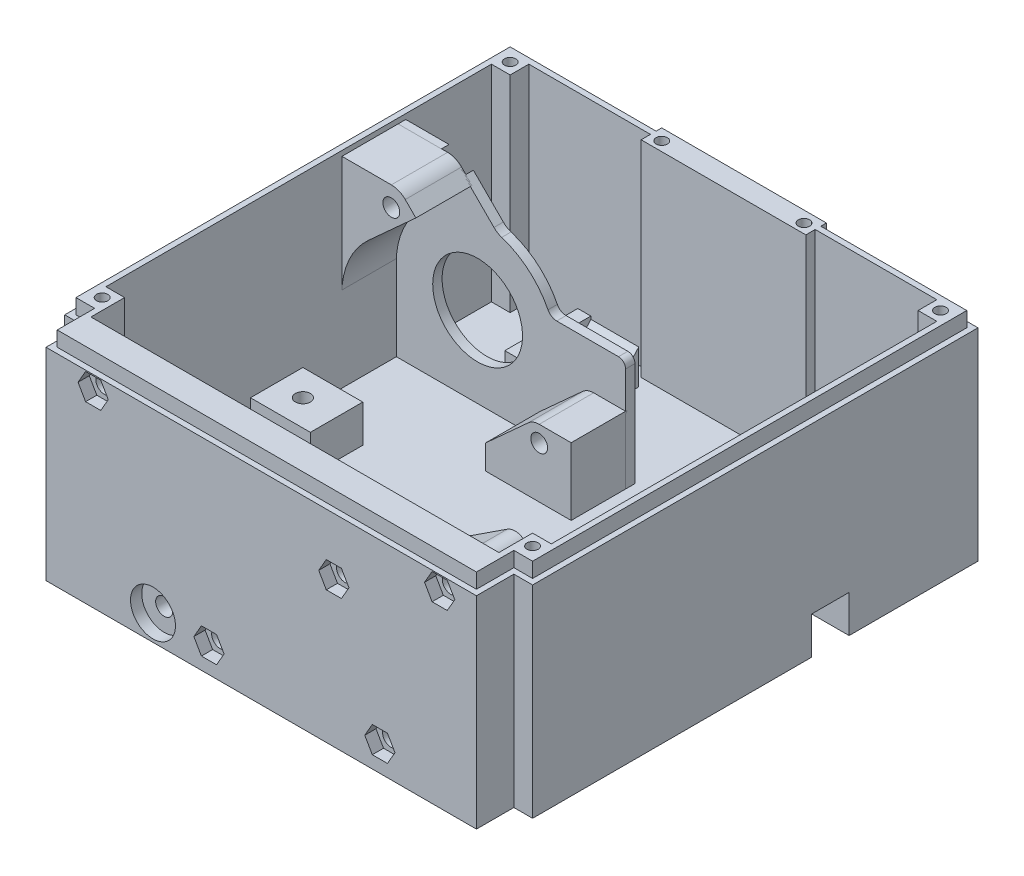
SolidWorks part; units mm, degrees
material "ABS"
ref_plane "Front Plane" through (0, 0, 0) normal (0, 0, 1) x (1, 0, 0)
ref_plane "Top Plane" through (0, 0, 0) normal (0, 1, 0) x (1, 0, 0)
ref_plane "Right Plane" through (0, 0, 0) normal (1, 0, 0) x (0, 0, -1)
sketch "Sketch1" plane through (0, 0, 0) normal (0, 1, 0) x (1, 0, 0)
  line L1 (-62.5, -64.5) -> (62.5, -64.5)
  line L2 (-62.5, -64.5) -> (-62.5, 64.5)
  line L3 (-62.5, 64.5) -> (62.5, 64.5)
  line L4 (62.5, -64.5) -> (62.5, 64.5)
  line L5 (-62.5, -64.5) -> (62.5, 64.5) construction
  line L6 (-62.5, 64.5) -> (62.5, -64.5) construction
  line L7 (-62.5, -54.5) -> (-57.5, -54.5)
  line L8 (-62.5, -54.5) -> (-62.5, -64.5)
  line L9 (-62.5, -64.5) -> (-57.5, -64.5)
  line L10 (-57.5, -54.5) -> (-57.5, -64.5)
  line L11 (62.5, -54.5) -> (57.5, -54.5)
  line L12 (62.5, -54.5) -> (62.5, -64.5)
  line L13 (62.5, -64.5) -> (57.5, -64.5)
  line L14 (57.5, -54.5) -> (57.5, -64.5)
  point P0 (0, 0)
  dimension "D1" = 129
  dimension "D2" = 125
  dimension "D3" = 10
  dimension "D4" = 5
  dimension "D5" = 10
  dimension "D6" = 5
extrude "Boss-Extrude1" add sketch "Sketch1" along normal blind 3 contours L14 L11 L4 L3 L2 L7 L10 L1
sketch "Sketch2" plane through (0, 3, 0) normal (0, 1, 0) x (1, 0, 0)
  line L0 (-59.5, 61.5) -> (59.5, 61.5)
  line L1 (-59.5, 61.5) -> (-59.5, -51.5)
  line L2 (-59.5, -51.5) -> (-54.5, -51.5)
  line L3 (-54.5, -51.5) -> (-54.5, -58.5)
  line L4 (-54.5, -58.5) -> (54.5, -58.5)
  line L5 (54.5, -58.5) -> (54.5, -51.5)
  line L6 (54.5, -51.5) -> (59.5, -51.5)
  line L7 (59.5, -51.5) -> (59.5, 61.5)
  line L8 (57.5, -64.5) -> (57.5, -54.5)
  line L9 (57.5, -54.5) -> (62.5, -54.5)
  line L10 (62.5, -54.5) -> (62.5, 64.5)
  line L11 (62.5, 64.5) -> (-62.5, 64.5)
  line L12 (-62.5, 64.5) -> (-62.5, -54.5)
  line L13 (-62.5, -54.5) -> (-57.5, -54.5)
  line L14 (-57.5, -54.5) -> (-57.5, -64.5)
  line L15 (-57.5, -64.5) -> (57.5, -64.5)
  line L16 (57.5, -64.5) -> (57.5, -54.5)
  line L17 (57.5, -54.5) -> (62.5, -54.5)
  line L18 (62.5, -54.5) -> (62.5, 64.5)
  line L19 (62.5, 64.5) -> (-62.5, 64.5)
  line L20 (-62.5, 64.5) -> (-62.5, -54.5)
  line L21 (-62.5, -54.5) -> (-57.5, -54.5)
  line L22 (-57.5, -54.5) -> (-57.5, -64.5)
  line L23 (-57.5, -64.5) -> (57.5, -64.5)
  line L24 (0, 95.4757) -> (0, 21.0279) construction
  line L25 (-59.5, 61.5) -> (-54.5, 61.5)
  line L26 (-59.5, 61.5) -> (-59.5, 56.5)
  line L27 (-59.5, 56.5) -> (-54.5, 56.5)
  line L28 (-54.5, 61.5) -> (-54.5, 56.5)
  line L29 (59.5, 56.5) -> (54.5, 56.5)
  line L30 (54.5, 61.5) -> (54.5, 56.5)
  line L31 (59.5, 61.5) -> (54.5, 61.5)
  line L32 (59.5, 61.5) -> (59.5, 56.5)
  line L34 (-54.5, -51.5) -> (-59.5, -51.5)
  line L35 (-54.5, -51.5) -> (-54.5, -46.5)
  line L36 (-54.5, -46.5) -> (-59.5, -46.5)
  line L37 (-59.5, -51.5) -> (-59.5, -46.5)
  line L38 (54.5, -51.5) -> (59.5, -51.5)
  line L39 (54.5, -51.5) -> (54.5, -46.5)
  line L40 (54.5, -46.5) -> (59.5, -46.5)
  line L41 (59.5, -51.5) -> (59.5, -46.5)
  line L42 (22, 61.5) -> (-22, 61.5)
  line L43 (22, 61.5) -> (22, 59)
  line L44 (22, 59) -> (-22, 59)
  line L45 (-22, 61.5) -> (-22, 59)
  circle A0 centre (-57.5, 59.5) radius 1.5
  circle A1 centre (57.5, 59.5) radius 1.5
  circle A2 centre (-57.5, -49.5) radius 1.5
  circle A3 centre (57.5, -49.5) radius 1.5
  circle A4 centre (-19, 61.5) radius 1.5
  circle A5 centre (19, 61.5) radius 1.5
  point P40 (0, 59)
  dimension "D12" = 3
  dimension "D19" = 3
  dimension "D20" = 3
  dimension "D27" = 3
  dimension "D28" = 3
  dimension "D2" = 3
  dimension "D3" = 3
  dimension "D4" = 3
  dimension "D5" = 3
  dimension "D6" = 3
  dimension "D7" = 6
  dimension "D8" = 3
  dimension "D9" = 3
  dimension "D10" = 5
  dimension "D11" = 5
  dimension "D13" = 3
  dimension "D14" = 3
  dimension "D15" = 5
  dimension "D16" = 5
  dimension "D17" = 3
  dimension "D18" = 3
  dimension "D21" = 3
  dimension "D22" = 3
  dimension "D23" = 2.5
  dimension "D24" = 22
  dimension "D25" = 3
  dimension "D26" = 3
  dimension "D1" = 0
extrude "Boss-Extrude2" add sketch "Sketch2" along normal blind 55
sketch "Sketch14" plane through (0, 0, -31.119) normal (0, 0, -1) x (-1, 0, 0)
  line L0 (-1.7313, 24.25) -> (-1.7313, 3)
  line L1 (54.5, 3) -> (22, 3) construction
  line L2 (51.5558, 41.4884) -> (51.5558, 51.3861)
  line L3 (42.5935, 55.0985) -> (33.4381, 45.943)
  line L4 (51.5558, 41.4884) -> (51.5558, 51.3861)
  line L5 (42.5935, 55.0985) -> (33.4381, 45.943)
  line L6 (58.8568, 24.6361) -> (58.8568, 3)
  line L7 (-1.7313, 3) -> (58.8568, 3)
  line L8 (-1.7313, 30.7722) -> (-1.7313, 24.25)
  line L9 (0.1697, 22.349) -> (6.8497, 22.349)
  line L10 (10.614, 20.8948) -> (23.6529, 9.0528)
  line L11 (16.6825, 32.6732) -> (0.1697, 32.6732)
  line L12 (-1.7313, 30.7722) -> (-1.7313, 24.25)
  line L13 (0.1697, 22.349) -> (6.8497, 22.349)
  line L14 (10.614, 20.8948) -> (23.6529, 9.0528)
  line L15 (16.6825, 32.6732) -> (0.1697, 32.6732)
  line L16 (46.3058, 56.6362) -> (59.9736, 56.6362)
  line L17 (-1.6185, 22.2795) -> (2.0476, 14.4174)
  line L18 (10.5181, 12.9238) -> (10.8691, 13.2747)
  line L19 (11.5762, 13.5676) -> (16.8614, 13.5676)
  line L20 (18.205, 13.0492) -> (10.1644, 20.3401)
  line L21 (6.8059, 21.6361) -> (0.0557, 21.6361)
  line L22 (-1.5958, 23.5453) -> (2.0476, 14.4174)
  line L23 (10.5181, 12.9238) -> (10.8691, 13.2747)
  line L24 (11.5762, 13.5676) -> (16.8614, 13.5676)
  line L27 (58.8568, 3) -> (59.9736, 3)
  line L28 (58.8568, 3) -> (58.8568, 24.6361)
  line L29 (58.8568, 24.6361) -> (59.9736, 24.6361)
  line L30 (59.9736, 3) -> (59.9736, 24.6361)
  line L31 (59.9736, 56.6362) -> (59.9736, 24.6361)
  arc A0 (16.8614, 13.5676) -> (20.0293, 12.3438) centre (16.8614, 8.8557) cw
  arc A1 (2.0476, 14.4174) -> (10.5181, 12.9238) centre (6.8058, 16.6361) ccw
  arc A2 (51.5558, 41.4884) -> (33.4381, 45.943) centre (37.8058, 24.6361) ccw
  arc A3 (51.5558, 51.3861) -> (42.5935, 55.0985) centre (46.3058, 51.3861) ccw
  arc A5 (51.5558, 51.3861) -> (42.5935, 55.0985) centre (46.3058, 51.3861) ccw
  arc A6 (2.0476, 14.4174) -> (10.5181, 12.9238) centre (6.8058, 16.6361) ccw
  arc A7 (33.4381, 45.943) -> (31.3659, 44.6779) centre (29.7858, 49.5953) cw
  arc A8 (51.5558, 41.4884) -> (52.2034, 39.9936) centre (53.6048, 41.4884) ccw
  arc A9 (-1.7313, 24.25) -> (0.1697, 22.349) centre (0.1697, 24.25) ccw
  arc A10 (10.614, 20.8948) -> (6.8497, 22.349) centre (6.8497, 16.75) ccw
  arc A11 (23.6529, 9.0528) -> (19.0038, 34.1034) centre (37.8058, 24.6361) ccw
  arc A12 (16.6825, 32.6732) -> (19.0038, 34.1034) centre (16.6825, 35.2722) ccw
  arc A13 (0.1697, 32.6732) -> (-1.7313, 30.7722) centre (0.1697, 30.7722) ccw
  arc A14 (-1.7313, 24.25) -> (0.1697, 22.349) centre (0.1697, 24.25) ccw
  arc A15 (10.614, 20.8948) -> (6.8497, 22.349) centre (6.8497, 16.75) ccw
  arc A16 (23.6529, 9.0528) -> (19.0038, 34.1034) centre (37.8058, 24.6361) ccw
  arc A17 (16.6825, 32.6732) -> (19.0038, 34.1034) centre (16.6825, 35.2722) ccw
  arc A18 (0.1697, 32.6732) -> (-1.7313, 30.7722) centre (0.1697, 30.7722) ccw
  arc A19 (44.0589, 51.5039) -> (48.5527, 51.2684) centre (46.3058, 51.3861) ccw construction
  arc A20 (44.0589, 51.5039) -> (48.5527, 51.2684) centre (46.3058, 51.3861) ccw
  arc A21 (48.5527, 51.2684) -> (44.0589, 51.5039) centre (46.3058, 51.3861) ccw construction
  arc A22 (48.5527, 51.2684) -> (44.0589, 51.5039) centre (46.3058, 51.3861) ccw
  arc A23 (4.5589, 16.7539) -> (9.0527, 16.5184) centre (6.8058, 16.6361) ccw construction
  arc A24 (9.0527, 16.5184) -> (4.5589, 16.7539) centre (6.8058, 16.6361) ccw construction
  arc A25 (4.5589, 16.7539) -> (9.0527, 16.5184) centre (6.8058, 16.6361) ccw
  arc A26 (9.0527, 16.5184) -> (4.5589, 16.7539) centre (6.8058, 16.6361) ccw
  circle A27 centre (37.8058, 24.6361) radius 12
  ellipse E4 centre (11.5764, 12.5676) end of major axis (10.6988, 13.0474) minor radius 1 (11.5762, 13.5676) -> (10.8691, 13.2747) ccw
  ellipse E5 centre (16.8611, 11.5675) end of major axis (18.6261, 12.509) minor radius 2 (18.205, 13.0492) -> (16.8614, 13.5676) ccw
  ellipse E6 centre (6.8057, 16.6359) end of major axis (8.6058, 21.3009) minor radius 5 (10.1644, 20.3401) -> (6.8059, 21.6361) ccw
  ellipse E7 centre (0.0559, 24.1362) end of major axis (-1.712, 22.3683) minor radius 2.5 (-1.6185, 22.2795) -> (0.0557, 21.6361) ccw
  ellipse E8 centre (11.5764, 12.5676) end of major axis (10.6988, 13.0474) minor radius 1 (11.5762, 13.5676) -> (10.8691, 13.2747) ccw
  dimension "D4" = 24
  dimension "D1" = 0
  dimension "D2" = 0
  dimension "D3" = 0
extrude "Boss-Extrude10" add sketch "Sketch14" along normal blind 2.5 separate body contours L15 A18 L12 A14 L13 A15 L14 A16 A17 | E8 L24 A0 L14 A15 L13 A14 L22 A6 L23 A26 A25 | A16 A8 L4 A5 L5 A7 A22 A20 | L24 E8 L23 A6 L22 A14 L0 L7 L6 A16 L14 A0 | L27 L30 L29 L6 | A16 L29 L31 L16 A5 L4 A8
sketch "Sketch21" plane through (0, 0, -16.569) normal (0, 0, -1) x (-1, 0, 0)
  line L0 (59.9736, 56.6362) -> (46.3058, 56.6362)
  line L1 (59.9736, 56.6362) -> (59.9736, 24.6361)
  line L2 (51.5558, 41.4884) -> (51.5558, 51.3861)
  line L3 (42.5935, 55.0985) -> (33.4381, 45.943)
  line L5 (42.5935, 55.0985) -> (33.4381, 45.943)
  line L6 (59.9736, 56.6362) -> (59.9736, 3) construction
  line L7 (59.9736, 24.6361) -> (59.5558, 24.6361)
  line L8 (-1.7313, 3) -> (-1.7313, 20.9902)
  line L9 (-1.7313, 30.7722) -> (-1.7313, 3) construction
  line L10 (-1.7313, 20.9902) -> (8.4879, 20.9902)
  line L11 (8.4879, 20.9902) -> (21.1422, 9.4976)
  line L12 (21.1422, 9.4976) -> (21.1422, 3)
  line L13 (-1.7313, 3) -> (59.9736, 3) construction
  line L14 (10.2113, 20.4513) -> (23.2502, 8.6093) construction
  line L15 (-1.7313, 3) -> (21.1422, 3)
  line L16 (52.4286, 40.7369) -> (39.7483, 52.2533)
  circle A0 centre (37.8058, 24.6361) radius 21.75
  arc A1 (9.7331, 19.8593) -> (6.8058, 20.9902) centre (6.8058, 16.6361) ccw
  arc A2 (51.5558, 41.4884) -> (33.4381, 45.943) centre (37.8058, 24.6361) ccw
  arc A3 (51.5558, 51.3861) -> (42.5935, 55.0985) centre (46.3058, 51.3861) ccw
  arc A4 (51.5558, 41.4884) -> (33.4381, 45.943) centre (37.8058, 24.6361) ccw
  arc A5 (51.5558, 51.3861) -> (42.5935, 55.0985) centre (46.3058, 51.3861) ccw
  circle A6 centre (6.8058, 16.6361) radius 2.25 construction
  circle A7 centre (6.8058, 16.6361) radius 2.25
  circle A9 centre (46.3058, 51.3861) radius 2.25
  arc M5 (33.4381, 45.943) -> (51.5558, 41.4884) centre (37.8058, 24.6361) cw
  line M6 (51.5558, 41.4884) -> (51.5558, 51.3861)
  arc M7 (51.5558, 51.3861) -> (42.5935, 55.0985) centre (46.3058, 51.3861) ccw
  line M8 (42.5935, 55.0985) -> (33.4381, 45.943)
  arc M9 (49.7111, 51.2076) -> (42.9005, 51.5646) centre (46.3058, 51.3861) cw
  arc M10 (42.9005, 51.5646) -> (49.7111, 51.2076) centre (46.3058, 51.3861) cw
  dimension "D1" = 0
extrude "Boss-Extrude11" add sketch "Sketch21" along normal blind 15 separate body contours A0 L7 L1 L0 M7 M6 | M8 M5 M6 M7 M10 M9 | L11 A1 L10 L8 L15 L12 | A9 M9 M10
sketch "Sketch30" plane through (0, 0, 58.5) normal (0, 0, -1) x (-1, 0, 0)
  line L0 (54.5, 3) -> (-54.5, 3) construction
  line L1 (54.5, 58) -> (-54.5, 58)
  line L2 (54.5, 58) -> (54.5, 3)
  line L3 (54.5, 3) -> (-54.5, 3)
  line L4 (-54.5, 58) -> (-54.5, 3)
  line L5 (48.5534, 51.2643) -> (53.7862, 33.4598) construction
  line L6 (27.2821, 43.2202) -> (42.8125, 53.3785) construction
  line L7 (25.2676, 5.7357) -> (20.0348, 23.5402) construction
  line L8 (46.5389, 13.7798) -> (31.0085, 3.6215) construction
  line L9 (-20.0651, 19.881) -> (-23.1574, 38.1791) construction
  line L10 (-18.9219, 42.5938) -> (-0.5115, 40.2621) construction
  line L11 (14.622, 25.743) -> (17.7143, 7.4449) construction
  line L12 (13.4789, 3.0302) -> (-4.9316, 5.3619) construction
  line L13 (48.5534, 51.2643) -> (53.7862, 33.4598)
  line L14 (27.2821, 43.2202) -> (42.8125, 53.3785)
  line L15 (26.0716, 3) -> (9.9069, 58)
  line L16 (46.5389, 13.7798) -> (30.0583, 3)
  line L17 (-20.0651, 19.881) -> (-23.1574, 38.1791)
  line L18 (-18.9219, 42.5938) -> (-0.5115, 40.2621)
  line L19 (14.622, 25.743) -> (18.4655, 3)
  line L20 (13.7173, 3) -> (-4.9316, 5.3619)
  line L21 (-54.5, 58) -> (-54.5, 3) construction
  line L22 (20.0348, 3) -> (12.801, 3) construction
  line L23 (13.7173, 3) -> (18.4655, 3)
  line L24 (23.0228, 3) -> (32.4348, 3) construction
  line L25 (26.0716, 3) -> (30.0583, 3)
  arc A0 (48.5534, 51.2643) -> (42.8125, 53.3785) centre (44.898, 50.19) ccw construction
  arc A1 (46.5389, 13.7798) -> (53.7862, 33.4598) centre (36.9105, 28.5) ccw construction
  arc A2 (27.2821, 43.2202) -> (20.0348, 23.5402) centre (36.9105, 28.5) ccw construction
  arc A4 (-18.9219, 42.5938) -> (-23.1574, 38.1791) centre (-19.4007, 38.814) ccw construction
  arc A5 (14.622, 25.743) -> (-0.5115, 40.2621) centre (-2.7215, 22.812) ccw construction
  arc A7 (-20.0651, 19.881) -> (-4.9316, 5.3619) centre (-2.7215, 22.812) ccw construction
  arc A8 (48.5534, 51.2643) -> (42.8125, 53.3785) centre (44.898, 50.19) ccw
  arc A9 (46.5389, 13.7798) -> (53.7862, 33.4598) centre (36.9105, 28.5) ccw
  arc A10 (27.2821, 43.2202) -> (20.0348, 23.5402) centre (36.9105, 28.5) ccw
  arc A12 (-18.9219, 42.5938) -> (-23.1574, 38.1791) centre (-19.4007, 38.814) ccw
  arc A13 (14.622, 25.743) -> (-0.5115, 40.2621) centre (-2.7215, 22.812) ccw
  arc A15 (-20.0651, 19.881) -> (-4.9316, 5.3619) centre (-2.7215, 22.812) ccw
extrude "Boss-Extrude18" add sketch "Sketch30" along normal blind 3
sketch "Sketch22" plane through (0, 58, 0) normal (0, 1, 0) x (1, 0, 0)
  line L0 (62.5, 64.5) -> (22, 64.5)
  line L1 (62.5, 64.5) -> (-62.5, 64.5) construction
  line L4 (-22, 64.5) -> (-62.5, 64.5)
  line L5 (22, 61.5) -> (22, 59) construction
  line L6 (-22, 61.5) -> (-22, 59) construction
  line L8 (-57.5, -64.5) -> (57.5, -64.5)
  line L9 (57.5, -64.5) -> (57.5, -54.5)
  line L10 (57.5, -54.5) -> (62.5, -54.5)
  line L11 (62.5, -54.5) -> (62.5, 64.5)
  line L12 (62.5, 64.5) -> (-62.5, 64.5)
  line L13 (-62.5, 64.5) -> (-62.5, -54.5)
  line L14 (-62.5, -54.5) -> (-57.5, -54.5)
  line L15 (-57.5, -54.5) -> (-57.5, -64.5)
  line L16 (-57.5, -64.5) -> (57.5, -64.5)
  line L17 (57.5, -64.5) -> (57.5, -54.5)
  line L18 (57.5, -54.5) -> (62.5, -54.5)
  line L19 (62.5, -54.5) -> (62.5, 64.5)
  line L21 (-62.5, 64.5) -> (-62.5, -54.5)
  line L22 (-62.5, -54.5) -> (-57.5, -54.5)
  line L23 (-57.5, -54.5) -> (-57.5, -64.5)
  dimension "D1" = 0
extrude "Cut-Extrude-Thin2" cut sketch "Sketch22" against normal blind 4 and the other way through all thin thin type one direction reverse wall 1.5
surface "Surface-Offset1" parameters "D1"=0
sketch "Sketch23" plane through (0, 3, 0) normal (0, 1, 0) x (1, 0, 0)
  line L0 (0, 65.3767) -> (0, 34.5683) construction
  line L5 (20.1448, 56.5) -> (20.1448, 37)
  line L6 (32.9297, 37) -> (20.1448, 37)
  line L7 (32.9297, 56.5) -> (32.9297, 37)
  line L8 (32.9297, 56.5) -> (20.1448, 56.5)
  line L10 (-32.9297, 56.5) -> (-20.1448, 56.5)
  line L11 (-32.9297, 56.5) -> (-32.9297, 37)
  line L12 (-32.9297, 37) -> (-20.1448, 37)
  line L13 (-20.1448, 56.5) -> (-20.1448, 37)
  line L14 (-32.9297, 59.0019) -> (-32.9297, 34.9481) construction
sketch "Sketch26" plane through (0, 0, 58.5) normal (0, 0, -1) x (-1, 0, 0)
  line L0 (-35.0379, 3) -> (-26.4738, 3) construction
  line L1 (-22, 3) -> (-54.5, 3) construction
  line L2 (-32.8358, 3) -> (-28.8491, 3)
  line L4 (-28.0451, 5.7357) -> (-22.8123, 23.5402)
  line L5 (-49.3164, 13.7798) -> (-33.786, 3.6215)
  line L6 (-51.3309, 51.2643) -> (-56.5637, 33.4598)
  line L7 (-30.0596, 43.2202) -> (-45.59, 53.3785)
  line L8 (-28.8491, 3) -> (-22.8123, 23.5402)
  line L9 (-49.3164, 13.7798) -> (-32.8358, 3)
  line L10 (-51.3309, 51.2643) -> (-56.5637, 33.4598)
  line L11 (-30.0596, 43.2202) -> (-45.59, 53.3785)
  arc A4 (-33.786, 3.6215) -> (-28.0451, 5.7357) centre (-31.7005, 6.81) ccw
  arc A5 (-56.5637, 33.4598) -> (-49.3164, 13.7798) centre (-39.688, 28.5) ccw
  arc A6 (-45.59, 53.3785) -> (-51.3309, 51.2643) centre (-47.6755, 50.19) ccw
  arc A7 (-22.8123, 23.5402) -> (-30.0596, 43.2202) centre (-39.688, 28.5) ccw
  arc A9 (-56.5637, 33.4598) -> (-49.3164, 13.7798) centre (-39.688, 28.5) ccw
  arc A10 (-45.59, 53.3785) -> (-51.3309, 51.2643) centre (-47.6755, 50.19) ccw
  arc A11 (-22.8123, 23.5402) -> (-30.0596, 43.2202) centre (-39.688, 28.5) ccw
  dimension "D1" = 0
extrude "Boss-Extrude14" add sketch "Sketch26" along normal blind 14.15 contours A9 L9 L2 L8 A11 L11 A10 L10
sketch "Sketch9" plane through (0, 0, 64.5) normal (0, 0, 1) x (1, 0, 0)
  arc A24 (-42.7529, 50.98) -> (-47.0432, 49.4) centre (-44.898, 50.19) ccw construction
  arc A25 (-47.0432, 49.4) -> (-42.7529, 50.98) centre (-44.898, 50.19) ccw construction
  arc A26 (-42.7529, 50.98) -> (-47.0432, 49.4) centre (-44.898, 50.19) ccw
  arc A27 (-47.0432, 49.4) -> (-42.7529, 50.98) centre (-44.898, 50.19) ccw
  arc A28 (-31.0681, 6.02) -> (-26.7778, 7.6) centre (-28.923, 6.81) ccw construction
  arc A29 (-26.7778, 7.6) -> (-31.0681, 6.02) centre (-28.923, 6.81) ccw construction
  arc A30 (-31.0681, 6.02) -> (-26.7778, 7.6) centre (-28.923, 6.81) ccw
  arc A31 (-26.7778, 7.6) -> (-31.0681, 6.02) centre (-28.923, 6.81) ccw
  arc A32 (-15.5402, 8.4596) -> (-12.375, 5.1604) centre (-13.9576, 6.81) ccw construction
  arc A33 (-12.375, 5.1604) -> (-15.5402, 8.4596) centre (-13.9576, 6.81) ccw construction
  arc A34 (-15.5402, 8.4596) -> (-12.375, 5.1604) centre (-13.9576, 6.81) ccw
  arc A35 (-12.375, 5.1604) -> (-15.5402, 8.4596) centre (-13.9576, 6.81) ccw
  arc A36 (20.9833, 37.1644) -> (17.818, 40.4636) centre (19.4007, 38.814) ccw construction
  arc A37 (17.818, 40.4636) -> (20.9833, 37.1644) centre (19.4007, 38.814) ccw construction
  arc A38 (20.9833, 37.1644) -> (17.818, 40.4636) centre (19.4007, 38.814) ccw
  arc A39 (17.818, 40.4636) -> (20.9833, 37.1644) centre (19.4007, 38.814) ccw
  arc A40 (29.5553, 7.6) -> (33.8456, 6.02) centre (31.7005, 6.81) ccw construction
  arc A41 (33.8456, 6.02) -> (29.5553, 7.6) centre (31.7005, 6.81) ccw construction
  arc A42 (29.5553, 7.6) -> (33.8456, 6.02) centre (31.7005, 6.81) ccw
  arc A43 (33.8456, 6.02) -> (29.5553, 7.6) centre (31.7005, 6.81) ccw
  arc A44 (49.8207, 49.4) -> (45.5304, 50.98) centre (47.6755, 50.19) ccw construction
  arc A45 (45.5304, 50.98) -> (49.8207, 49.4) centre (47.6755, 50.19) ccw construction
  arc A46 (49.8207, 49.4) -> (45.5304, 50.98) centre (47.6755, 50.19) ccw
  arc A47 (45.5304, 50.98) -> (49.8207, 49.4) centre (47.6755, 50.19) ccw
extrude "Cut-Extrude7" cut sketch "Sketch9" against normal blind 23
sketch "Sketch24" plane through (0, 0, 64.5) normal (0, 0, 1) x (1, 0, 0)
  line L7 (-40.8566, 50.19) -> (-42.8773, 53.69)
  line L8 (-42.8773, 53.69) -> (-46.9188, 53.69)
  line L9 (-46.9188, 53.69) -> (-48.9395, 50.19)
  line L10 (-48.9395, 50.19) -> (-46.9188, 46.69)
  line L11 (-46.9188, 46.69) -> (-42.8773, 46.69)
  line L12 (-42.8773, 46.69) -> (-40.8566, 50.19)
  line L13 (51.717, 50.19) -> (49.6963, 53.69)
  line L14 (49.6963, 53.69) -> (45.6548, 53.69)
  line L15 (45.6548, 53.69) -> (43.6341, 50.19)
  line L16 (43.6341, 50.19) -> (45.6548, 46.69)
  line L17 (45.6548, 46.69) -> (49.6963, 46.69)
  line L18 (49.6963, 46.69) -> (51.717, 50.19)
  line L19 (35.7419, 6.81) -> (33.7212, 10.31)
  line L20 (33.7212, 10.31) -> (29.6797, 10.31)
  line L21 (29.6797, 10.31) -> (27.659, 6.81)
  line L22 (27.659, 6.81) -> (29.6797, 3.31)
  line L23 (29.6797, 3.31) -> (33.7212, 3.31)
  line L24 (33.7212, 3.31) -> (35.7419, 6.81)
  line L25 (-9.9161, 6.81) -> (-11.9368, 10.31)
  line L26 (-11.9368, 10.31) -> (-15.9783, 10.31)
  line L27 (-15.9783, 10.31) -> (-17.999, 6.81)
  line L28 (-17.999, 6.81) -> (-15.9783, 3.31)
  line L29 (-15.9783, 3.31) -> (-11.9368, 3.31)
  line L30 (-11.9368, 3.31) -> (-9.9161, 6.81)
  line L31 (23.4421, 38.814) -> (21.4214, 42.314)
  line L32 (21.4214, 42.314) -> (17.3799, 42.314)
  line L33 (17.3799, 42.314) -> (15.3592, 38.814)
  line L34 (15.3592, 38.814) -> (17.3799, 35.314)
  line L35 (17.3799, 35.314) -> (21.4214, 35.314)
  line L36 (21.4214, 35.314) -> (23.4421, 38.814)
  circle A0 centre (-28.923, 6.81) radius 6
  circle A1 centre (-44.898, 50.19) radius 3.5 construction
  circle A2 centre (47.6755, 50.19) radius 3.5 construction
  circle A3 centre (31.7005, 6.81) radius 3.5 construction
  circle A4 centre (-13.9576, 6.81) radius 3.5 construction
  circle A5 centre (19.4007, 38.814) radius 3.5 construction
  dimension "D1" = 12
  dimension "D2" = 7
  dimension "D3" = 7
  dimension "D4" = 7
  dimension "D5" = 7
  dimension "D6" = 7
extrude "Cut-Extrude8" cut sketch "Sketch24" against normal blind 3
extrude "Boss-Extrude15" add sketch "Sketch23" along normal up to surface (9.2444 mm away)
sketch "Sketch28" plane through (0, 3, 0) normal (0, 1, 0) x (1, 0, 0)
  line L0 (-32.9297, 37) -> (-20.1448, 37) construction
  line L1 (-32.9297, 56.5) -> (-36.4297, 56.5)
  line L2 (-32.9297, 56.5) -> (-32.9297, 37)
  line L3 (-32.9297, 37) -> (-36.4297, 37)
  line L4 (-36.4297, 56.5) -> (-36.4297, 37)
  line L6 (32.9297, 56.5) -> (36.4297, 56.5)
  line L7 (32.9297, 56.5) -> (32.9297, 37)
  line L8 (32.9297, 37) -> (36.4297, 37)
  line L9 (36.4297, 56.5) -> (36.4297, 37)
  dimension "D1" = 3.5
  dimension "D2" = 3.5
extrude "Boss-Extrude16" add sketch "Sketch28" along normal blind 10
sketch "Sketch29" plane through (0, 0, -37) normal (0, 0, 1) x (1, 0, 0)
  line L1 (-29.8007, 3.0145) -> (-23.8007, 3.0145)
  line L2 (-29.8007, 3.0145) -> (-29.8007, 5.5145)
  line L3 (-29.8007, 5.5145) -> (-23.8007, 5.5145)
  line L4 (-23.8007, 3.0145) -> (-23.8007, 5.5145)
  line L5 (23.9025, 3.0145) -> (29.9025, 3.0145)
  line L6 (23.9025, 3.0145) -> (23.9025, 5.5145)
  line L7 (23.9025, 5.5145) -> (29.9025, 5.5145)
  line L8 (29.9025, 3.0145) -> (29.9025, 5.5145)
  dimension "D1" = 6
  dimension "D2" = 2.5
  dimension "D3" = 6
extrude "Cut-Extrude9" cut sketch "Sketch29" against normal blind 21
sketch "Sketch31" plane through (0, 0, -33.619) normal (0, 0, -1) x (-1, 0, 0)
  circle A0 centre (6.8058, 16.6361) radius 2.25 construction
  circle A1 centre (6.8058, 16.6361) radius 2.25
  circle A2 centre (6.8058, 16.6361) radius 5.5
  circle A4 centre (46.3058, 51.3861) radius 5.5
  dimension "D1" = 11
  dimension "D2" = 11
extrude "Cut-Extrude10" cut sketch "Sketch31" against normal blind 2
sketch "Sketch32" plane through (0, 3, 0) normal (0, 1, 0) x (1, 0, 0)
  line L0 (59.5, -46.5) -> (59.5, 56.5) construction
  line L1 (59.5, 33.0616) -> (43.5, 33.0616)
  line L2 (59.5, 33.0616) -> (59.5, 17.0616)
  line L3 (59.5, 17.0616) -> (43.5, 17.0616)
  line L4 (43.5, 33.0616) -> (43.5, 17.0616)
  line L5 (-59.5, 56.5) -> (-59.5, -46.5) construction
  line L6 (-59.5, 6.1291) -> (-43.5, 6.1291)
  line L7 (-59.5, 6.1291) -> (-59.5, -7.8709)
  line L8 (-59.5, -7.8709) -> (-43.5, -7.8709)
  line L9 (-43.5, 6.1291) -> (-43.5, -7.8709)
  line M22 (-59.5, 56.5) -> (-59.5, -46.5)
  dimension "D1" = 14
  dimension "D2" = 16
  dimension "D3" = 16
  dimension "D4" = 16
extrude "Boss-Extrude19" add sketch "Sketch32" along normal blind 10 contours L9 L6 L8 M22 | L4 L3 L2 L1
sketch "Sketch33" plane through (0, 0, 0) normal (0, -1, 0) x (1, 0, 0)
  line L0 (62.5, 54.5) -> (62.5, -64.5) construction
  line L1 (62.5, -20.0616) -> (46.5, -20.0616)
  line L2 (62.5, -20.0616) -> (62.5, -30.0616)
  line L3 (62.5, -30.0616) -> (46.5, -30.0616)
  line L4 (46.5, -20.0616) -> (46.5, -30.0616)
  line L5 (59.5, -33.0616) -> (43.5, -33.0616) construction
  line L6 (59.5, -17.0616) -> (43.5, -17.0616) construction
  line L7 (43.5, -33.0616) -> (43.5, -17.0616) construction
  line L8 (-62.5, -64.5) -> (-62.5, 54.5) construction
  line L9 (-62.5, -4.1291) -> (-46.5, -4.1291)
  line L10 (-62.5, -4.1291) -> (-62.5, 5.8709)
  line L11 (-62.5, 5.8709) -> (-46.5, 5.8709)
  line L12 (-46.5, -4.1291) -> (-46.5, 5.8709)
  line L13 (-43.5, -6.1291) -> (-43.5, 7.8709) construction
  line L14 (-59.5, -6.1291) -> (-43.5, -6.1291) construction
  line L15 (-59.5, 7.8709) -> (-43.5, 7.8709) construction
  dimension "D1" = 3
  dimension "D2" = 3
  dimension "D3" = 3
  dimension "D4" = 3
  dimension "D5" = 2
  dimension "D6" = 2
extrude "Cut-Extrude11" cut sketch "Sketch33" against normal blind 10
sketch "Sketch34" plane through (0, 13, 0) normal (0, 1, 0) x (1, 0, 0)
  line L0 (-71.8705, -0.8709) -> (-33.99, -0.8709) construction
  line L1 (-62.5, 4.1291) -> (-46.5, 4.1291) construction
  line L2 (-46.5, -5.8709) -> (-62.5, -5.8709) construction
  line L3 (-62.5, 4.1291) -> (-46.5, 4.1291)
  line L4 (-46.5, -5.8709) -> (-62.5, -5.8709)
  line L5 (-46.5, 4.1291) -> (-46.5, -5.8709) construction
  line L6 (46.5, 30.0616) -> (62.5, 30.0616) construction
  line L7 (62.5, 20.0616) -> (46.5, 20.0616) construction
  line L8 (46.5, 30.0616) -> (62.5, 30.0616)
  line L9 (62.5, 20.0616) -> (46.5, 20.0616)
  line L10 (37.5067, 25.0616) -> (69.8561, 25.0616) construction
  line L11 (46.5, 20.0616) -> (46.5, 30.0616) construction
  circle A0 centre (-52.5, -0.8709) radius 2
  circle A1 centre (52.5, 25.0616) radius 2
  dimension "D1" = 4
  dimension "D3" = 4
  dimension "D2" = 6
  dimension "D4" = 6
extrude "Cut-Extrude12" cut sketch "Sketch34" against normal blind 10 contours A1 | A0
